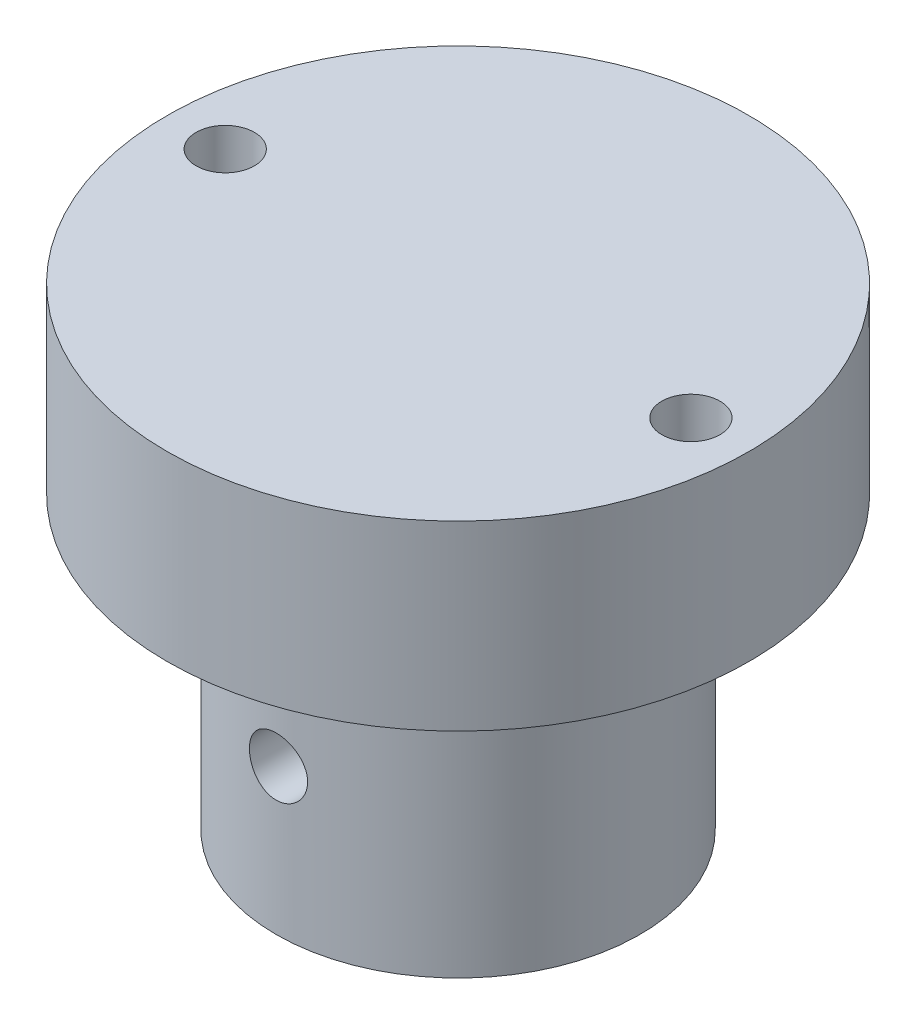
SolidWorks part; units mm, degrees
ref_plane "Front Plane" through (0, 0, 0) normal (0, 0, 1) x (1, 0, 0)
ref_plane "Top Plane" through (0, 0, 0) normal (0, 1, 0) x (1, 0, 0)
ref_plane "Right Plane" through (0, 0, 0) normal (1, 0, 0) x (0, 0, -1)
sketch "Sketch1" plane through (0, 0, 0) normal (0, 1, 0) x (1, 0, 0)
  circle A0 centre (0, 0) radius 6.35
  dimension "D1" = 12.7
extrude "Boss-Extrude1" add sketch "Sketch1" along normal blind 10.16
sketch "Sketch2" plane through (0, 10.16, 0) normal (0, 1, 0) x (1, 0, 0)
  circle A0 centre (0, 0) radius 4.7625
  dimension "D1" = 9.525
extrude "Cut-Extrude2" cut sketch "Sketch2" against normal up to surface (10.16 mm away) up to face at (0, 0, 6.35)
sketch "Sketch3" plane through (0, 10.16, 0) normal (0, 1, 0) x (1, 0, 0)
  circle A0 centre (0, 0) radius 6.35
  dimension "D1" = 12.7
extrude "Boss-Extrude2" add sketch "Sketch3" along normal blind 6.35
sketch "Sketch4" plane through (0, 0, 0) normal (0, 0, 1) x (1, 0, 0)
  line L0 (-4.7625, 0) -> (4.7625, 0) construction
  circle A0 centre (0, 5.08) radius 1.016
  dimension "D1" = 2.032
  dimension "D2" = 5.08
extrude "Cut-Extrude3" cut sketch "Sketch4" against normal up to surface and the other way up to surface up to face at (0, 0, 6.35) other way up to face at (0, 0, 6.35)
sketch "Sketch5" plane through (0, 16.51, 0) normal (0, 1, 0) x (1, 0, 0)
  circle A0 centre (0, 0) radius 10.16
  circle A1 centre (0, 0) radius 6.35
  dimension "D1" = 20.32
  dimension "D2" = 12.7
extrude "Boss-Extrude3" add sketch "Sketch5" against normal blind 6.35
sketch "Sketch10" plane through (0, 16.51, 0) normal (0, 1, 0) x (1, 0, 0)
  circle A0 centre (8.128, 0) radius 1.016
  circle A1 centre (-8.128, 0) radius 1.016
  circle A3 centre (0, 0) radius 10.16 construction
  dimension "D1" = 2.032
  dimension "D2" = 2.032
  dimension "D3" = 8.128
  dimension "D4" = 8.128
  dimension "D5" = 16.256
extrude "Cut-Extrude4" cut sketch "Sketch10" against normal up to surface (6.35 mm away) up to face at (0, 10.16, 6.35)
